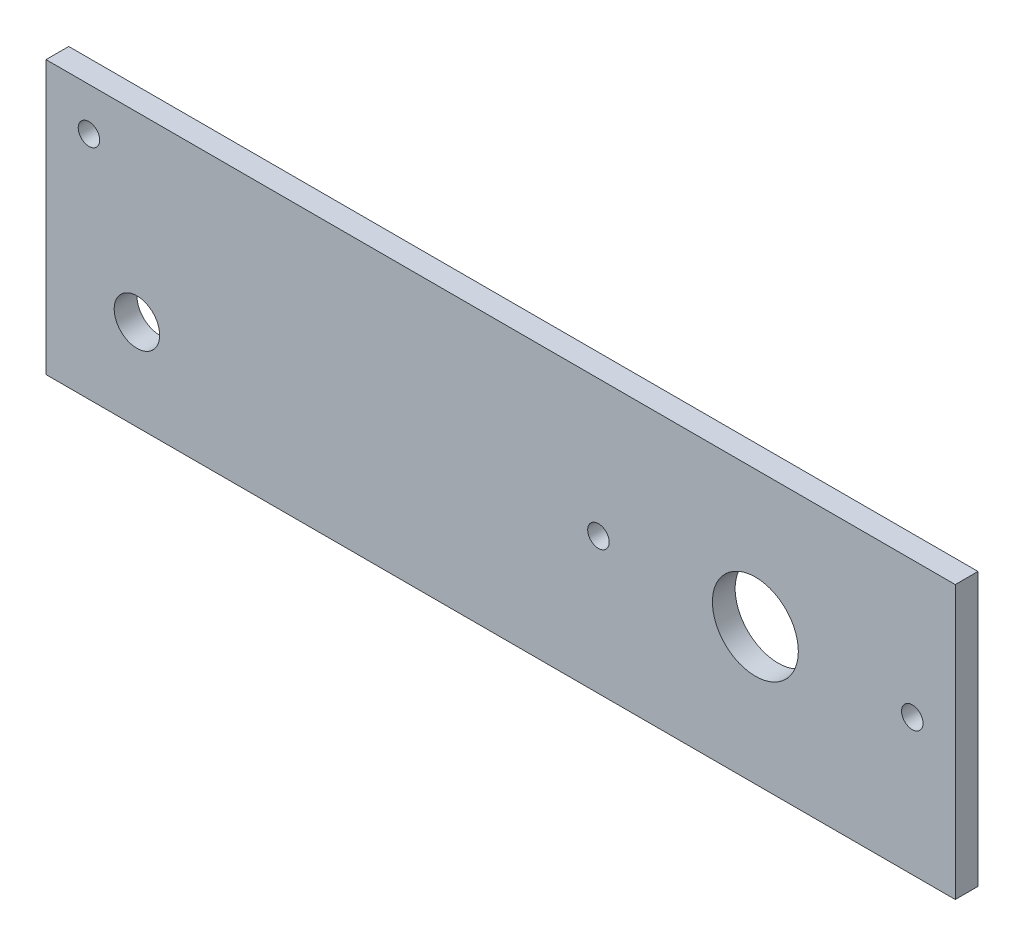
SolidWorks part; units mm, degrees
ref_plane "Front Plane" through (0, 0, 0) normal (0, 0, 1) x (1, 0, 0)
ref_plane "Top Plane" through (0, 0, 0) normal (0, 1, 0) x (1, 0, 0)
ref_plane "Right Plane" through (0, 0, 0) normal (1, 0, 0) x (0, 0, -1)
sketch "Sketch1" plane through (0, 0, 0) normal (1, 0, 0) x (0, 0, -1)
  line L1 (0, 0) -> (3.175, 0)
  line L2 (0, 0) -> (0, 38.1)
  line L3 (0, 38.1) -> (3.175, 38.1)
  line L4 (3.175, 0) -> (3.175, 38.1)
  dimension "D1" = 38.1
  dimension "D2" = 3.175
extrude "Boss-Extrude1" add sketch "Sketch1" along normal blind 127
sketch "Sketch2" plane through (0, 0, 0) normal (0, 0, 1) x (1, 0, 0)
  line L0 (127, 0) -> (0, 0) construction
  line L1 (0, 38.1) -> (0, 0) construction
  line L2 (127, 38.1) -> (127, 0) construction
  line L3 (77.1594, 19.05) -> (99.0797, 40.9703) construction
  line L4 (99.0797, 40.9703) -> (121, 19.05) construction
  line L5 (77.1594, 19.05) -> (99.0797, 19.05) construction
  line L6 (99.0797, 19.05) -> (121, 19.05) construction
  line L7 (127, 38.1) -> (0, 38.1) construction
  circle A0 centre (12.7, 12.7) radius 3.175
  circle A1 centre (121, 19.05) radius 1.5
  circle A2 centre (99.0797, 19.05) radius 6
  circle A3 centre (77.1594, 19.05) radius 1.5
  circle A4 centre (6, 32.1) radius 1.5
  point P14 (127, 19.05)
  dimension "D1" = 6.35
  dimension "D4" = 3
  dimension "D5" = 12
  dimension "D2" = 12.7
  dimension "D3" = 12.7
  dimension "D6" = 31
  dimension "D7" = 6
  dimension "D8" = 6
  dimension "D9" = 6
extrude "Cut-Extrude1" cut sketch "Sketch2" against normal through all
